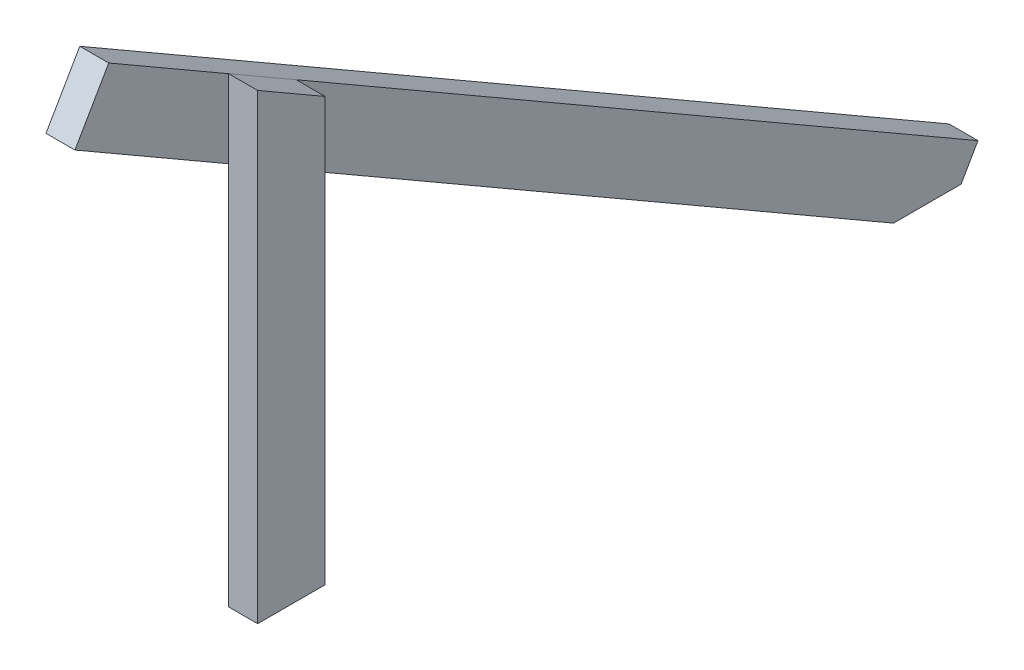
SolidWorks part; units mm, degrees
ref_plane "Front Plane" through (0, 0, 0) normal (0, 0, 1) x (1, 0, 0)
ref_plane "Top Plane" through (0, 0, 0) normal (0, 1, 0) x (1, 0, 0)
ref_plane "Right Plane" through (0, 0, 0) normal (1, 0, 0) x (0, 0, -1)
sketch "Sketch1" plane through (0, 0, 0) normal (1, 0, 0) x (0, 0, -1)
  line L0 (0, 0) -> (-1143.8464, 660.4)
  line L1 (0, 0) -> (-1181.8202, 0) construction
  dimension "D1" = 1320.8
  dimension "D2" = 30
other "Profiles 2X4(1)"
ref_plane "Plane1" through (0, 0, 0) normal (0, 0.5, 0.866) x (1, 0, 0)
sketch "2x4" plane through (0, 0, 0) normal (0, 0.5, 0.866) x (1, 0, 0)
  line L1 (-19.05, 44.45) -> (19.05, 44.45)
  line L2 (-19.05, 44.45) -> (-19.05, -44.45)
  line L3 (-19.05, -44.45) -> (19.05, -44.45)
  line L4 (19.05, 44.45) -> (19.05, -44.45)
  line L5 (-19.05, 44.45) -> (19.05, -44.45) construction
  line L6 (-19.05, -44.45) -> (19.05, 44.45) construction
  point P0 (0, 0)
  point P6 (0, 44.45)
  point P7 (-19.05, 0)
  point P8 (19.05, 0)
  point P9 (0, -44.45)
  point P10 (0, 0)
  dimension "D1" = 38.1
  dimension "D2" = 88.9
sketch "Sketch3" plane through (19.05, 0, 0) normal (1, 0, 0) x (0, 0, -1)
  line L0 (-919.3012, 530.7588) -> (-919.3012, 0)
  line L1 (0, 0) -> (-1143.8464, 660.4) construction
  line L2 (0, 0) -> (-1181.8202, 0) construction
other "Profiles 2X4(2)"
ref_plane "Plane2" through (38.1, 530.7588, 919.3012) normal (0, -1, 0) x (1, 0, 0)
sketch "2x41" plane through (38.1, 530.7588, 919.3012) normal (0, -1, 0) x (1, 0, 0)
  line L1 (-19.05, 44.45) -> (19.05, 44.45)
  line L2 (-19.05, 44.45) -> (-19.05, -44.45)
  line L3 (-19.05, -44.45) -> (19.05, -44.45)
  line L4 (19.05, 44.45) -> (19.05, -44.45)
  line L5 (-19.05, 44.45) -> (19.05, -44.45) construction
  line L6 (-19.05, -44.45) -> (19.05, 44.45) construction
  point P0 (0, 0)
  point P6 (0, 44.45)
  point P7 (-19.05, 0)
  point P8 (19.05, 0)
  point P9 (0, -44.45)
  point P10 (0, 0)
  dimension "D1" = 38.1
  dimension "D2" = 88.9
other "Trim/Extend1"
sketch "Sketch5" plane through (19.05, 0, 0) normal (1, 0, 0) x (0, 0, -1)
  line L0 (-764.9869, 0) -> (192.8098, 0)
  line L1 (0, 0) -> (-1181.8202, 0) construction
extrude "Cut-Extrude1" cut sketch "Sketch5" against normal through all and the other way through all flip side to cut
